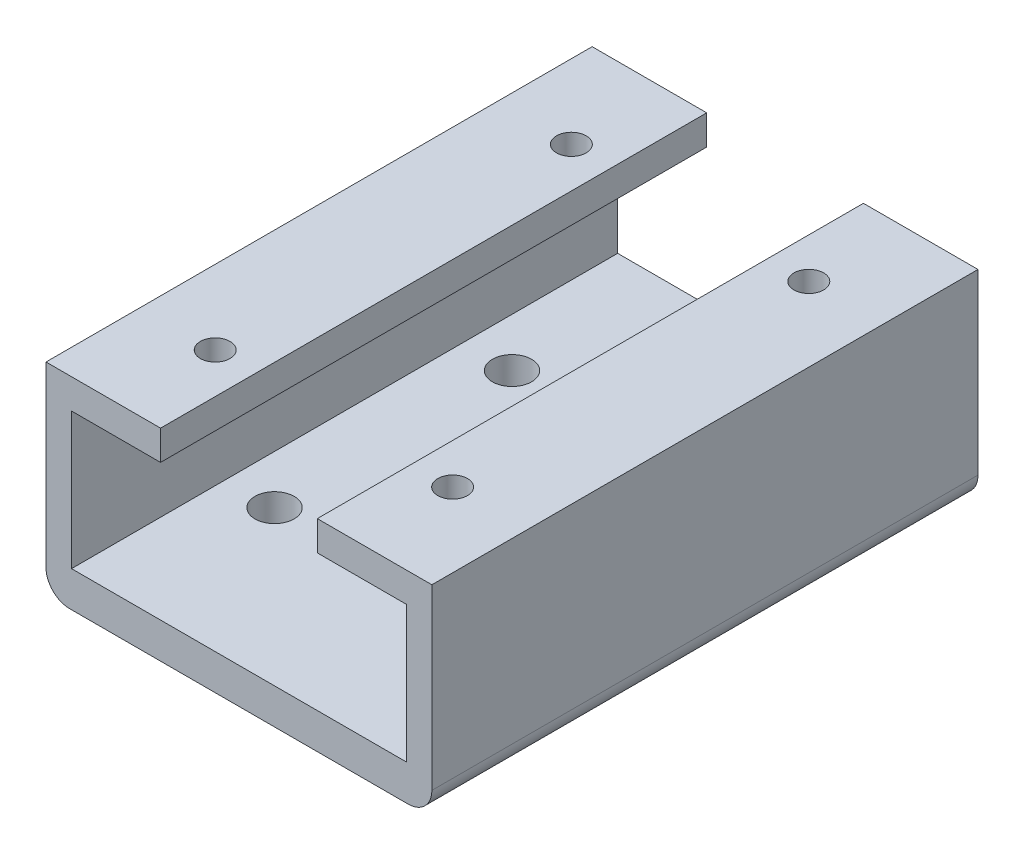
SolidWorks part; units mm, degrees
ref_plane "前视基准面" through (0, 0, 0) normal (0, 0, 1) x (1, 0, 0)
ref_plane "上视基准面" through (0, 0, 0) normal (0, 1, 0) x (1, 0, 0)
ref_plane "右视基准面" through (0, 0, 0) normal (1, 0, 0) x (0, 0, -1)
sketch "草图1" plane through (0, 0, 0) normal (0, 1, 0) x (1, 0, 0)
  line L1 (16.25, -23) -> (-16.25, -23)
  line L2 (16.25, -23) -> (16.25, 23)
  line L3 (16.25, 23) -> (-16.25, 23)
  line L4 (-16.25, -23) -> (-16.25, 23)
  line L5 (16.25, -23) -> (-16.25, 23) construction
  line L6 (16.25, 23) -> (-16.25, -23) construction
  point P0 (0, 0)
  dimension "D1" = 32.5
  dimension "D2" = 46
extrude "凸台-拉伸1" add sketch "草图1" along normal blind 17
sketch "草图2" plane through (0, 0, -23) normal (0, 0, -1) x (-1, 0, 0)
  line L0 (-16.25, 17) -> (16.25, 17) construction
  line L1 (-6.6, 14.5) -> (6.6, 14.5)
  line L2 (-6.6, 14.5) -> (-6.6, 17)
  line L3 (-6.6, 17) -> (6.6, 17)
  line L4 (6.6, 14.5) -> (6.6, 17)
  line L5 (-6.6, 14.5) -> (6.6, 17) construction
  line L6 (-6.6, 17) -> (6.6, 14.5) construction
  line L8 (-14.1, 3) -> (14.1, 3)
  line L9 (-14.1, 3) -> (-14.1, 14.5)
  line L10 (-14.1, 14.5) -> (14.1, 14.5)
  line L11 (14.1, 3) -> (14.1, 14.5)
  line L12 (-14.1, 3) -> (14.1, 14.5) construction
  line L13 (-14.1, 14.5) -> (14.1, 3) construction
  point P0 (0, 15.75)
  point P9 (0, 8.75)
  line M7 (16.25, 17) -> (-16.25, 17)
  dimension "D1" = 2.5
  dimension "D2" = 13.2
  dimension "D3" = 28.2
  dimension "D4" = 14
  dimension "D5" = 0
extrude "切除-拉伸2" cut sketch "草图2" against normal through all contours L1 L4 L2 M7 | L8 L11 L10 L1 L9
sketch "草图4" plane through (0, 0, 0) normal (0, -1, 0) x (1, 0, 0)
  line L1 (-10, -10) -> (10, -10) construction
  line L2 (-10, -10) -> (-10, 10) construction
  line L3 (-10, 10) -> (10, 10) construction
  line L4 (10, -10) -> (10, 10) construction
  line L5 (-10, -10) -> (10, 10) construction
  line L6 (-10, 10) -> (10, -10) construction
  circle A0 centre (-10, 10) radius 1.65
  circle A1 centre (10, 10) radius 1.65
  circle A2 centre (10, -10) radius 1.65
  circle A3 centre (-10, -10) radius 1.65
  point P0 (0, 0)
  dimension "D3" = 3.3
  dimension "D4" = 3.3
  dimension "D5" = 3.3
  dimension "D6" = 3.3
  dimension "D1" = 20
  dimension "D2" = 20
extrude "切除-拉伸3" cut sketch "草图4" against normal up to next
sketch "草图5" plane through (0, 17, 0) normal (0, 1, 0) x (1, 0, 0)
  line L1 (-10, -15) -> (10, -15) construction
  line L2 (-10, -15) -> (-10, 15) construction
  line L3 (-10, 15) -> (10, 15) construction
  line L4 (10, -15) -> (10, 15) construction
  line L5 (-10, -15) -> (10, 15) construction
  line L6 (-10, 15) -> (10, -15) construction
  circle A0 centre (-10, 15) radius 1.25
  circle A1 centre (10, 15) radius 1.25
  circle A2 centre (10, -15) radius 1.25
  circle A3 centre (-10, -15) radius 1.25
  point P0 (0, 0)
  dimension "D3" = 2.5
  dimension "D4" = 2.5
  dimension "D5" = 2.5
  dimension "D6" = 2.5
  dimension "D1" = 30
  dimension "D2" = 20
extrude "切除-拉伸4" cut sketch "草图5" against normal blind 2
fillet "圆角1" radius 2 2 edges at (16.25, 0, 0) (-16.25, 0, 0)
equation "\"33.5.00mm\"=34"
